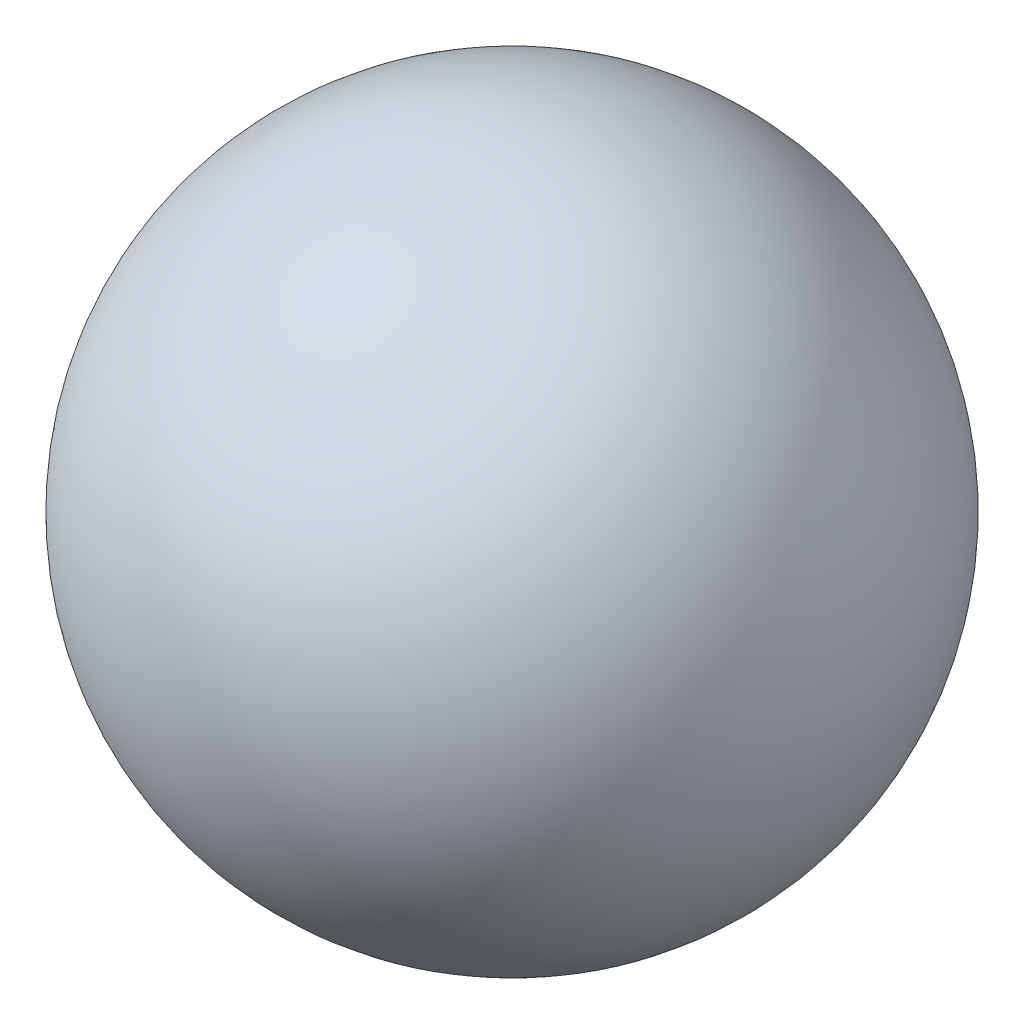
SolidWorks part; units mm, degrees
ref_plane "前视基准面" through (0, 0, 0) normal (0, 0, 1) x (1, 0, 0)
ref_plane "上视基准面" through (0, 0, 0) normal (0, 1, 0) x (1, 0, 0)
ref_plane "右视基准面" through (0, 0, 0) normal (1, 0, 0) x (0, 0, -1)
sketch "草图1" plane through (0, 0, 0) normal (0, 0, 1) x (1, 0, 0)
  line L0 (0, 21.25) -> (0, -21.25)
  arc A0 (0, -21.25) -> (0, 21.25) centre (0, 0) ccw
  dimension "D1" = 42.5
revolve "旋转1" add sketch "草图1" angle 360 about L0
